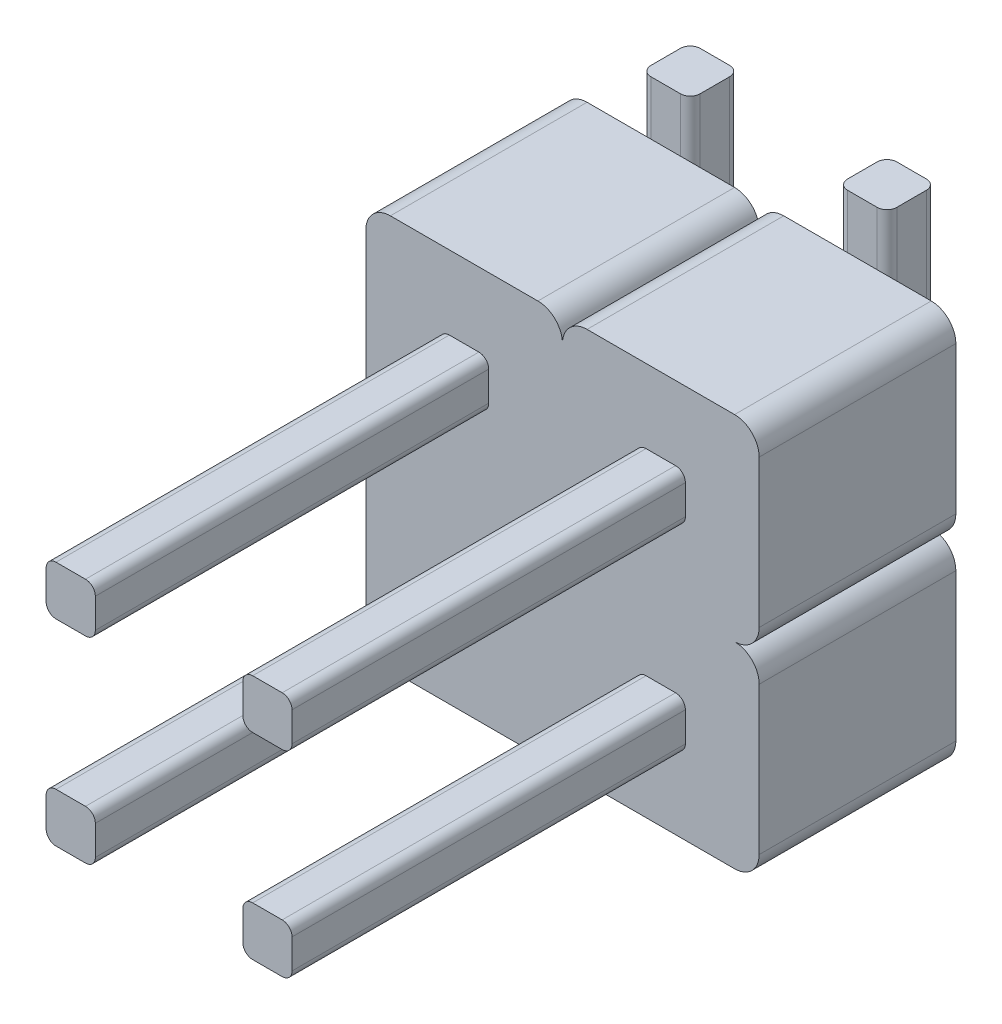
SolidWorks part; units mm, degrees
ref_plane "前视基准面" through (0, 0, 0) normal (0, 0, 1) x (1, 0, 0)
ref_plane "上视基准面" through (0, 0, 0) normal (0, 1, 0) x (1, 0, 0)
ref_plane "右视基准面" through (0, 0, 0) normal (1, 0, 0) x (0, 0, -1)
sketch "草图1" plane through (0, 0, 0) normal (0, 0, 1) x (1, 0, 0)
  line L0 (1, 0) -> (1, -2) construction
  line L1 (0.25, 0) -> (1.75, 0)
  line L2 (0, -0.25) -> (0, -1.75)
  line L3 (0.25, -2) -> (1.75, -2)
  line L4 (2, -0.25) -> (2, -1.75)
  line L5 (0, -1) -> (2, -1) construction
  line L7 (0.85, -0.75) -> (1.15, -0.75)
  line L8 (0.75, -0.85) -> (0.75, -1.15)
  line L9 (0.85, -1.25) -> (1.15, -1.25)
  line L10 (1.25, -0.85) -> (1.25, -1.15)
  arc A0 (2, -1.75) -> (1.75, -2) centre (1.75, -1.75) cw
  arc A1 (0.25, -2) -> (0, -1.75) centre (0.25, -1.75) cw
  arc A2 (0.25, 0) -> (0, -0.25) centre (0.25, -0.25) ccw
  arc A3 (2, -0.25) -> (1.75, 0) centre (1.75, -0.25) ccw
  circle A4 centre (1, -1) radius 0.25 construction
  arc A5 (0.75, -1.15) -> (0.85, -1.25) centre (0.85, -1.15) ccw
  arc A6 (1.15, -1.25) -> (1.25, -1.15) centre (1.15, -1.15) ccw
  arc A7 (1.25, -0.85) -> (1.15, -0.75) centre (1.15, -0.85) ccw
  arc A8 (0.85, -0.75) -> (0.75, -0.85) centre (0.85, -0.85) ccw
  point P11 (0, 0)
  dimension "D3" = 0.25
  dimension "D4" = 0.5
  dimension "D5" = 0.1
  dimension "D1" = 2
  dimension "D2" = 2
extrude "凸台-拉伸1" add sketch "草图1" along normal blind 2
sketch "草图2" plane through (0, 0, 2) normal (0, 0, 1) x (1, 0, 0)
  line L0 (0.75, -0.85) -> (0.75, -1.15)
  line L1 (0.85, -1.25) -> (1.15, -1.25)
  line L2 (1.25, -1.15) -> (1.25, -0.85)
  line L3 (1.15, -0.75) -> (0.85, -0.75)
  arc A0 (1.25, -1.15) -> (1.15, -1.25) centre (1.15, -1.15) cw
  arc A1 (0.85, -1.25) -> (0.75, -1.15) centre (0.85, -1.15) cw
  arc A2 (1.25, -0.85) -> (1.15, -0.75) centre (1.15, -0.85) ccw
  arc A3 (0.85, -0.75) -> (0.75, -0.85) centre (0.85, -0.85) ccw
  dimension "D1" = 0.1
extrude "凸台-拉伸2" add sketch "草图2" along normal blind 4 and the other way blind 2
pattern_linear "阵列(线性)2" count 2 spacing 2 along (1, 0, 0) count 2 spacing 2 along (0, -1, 0) of "凸台-拉伸1", "凸台-拉伸2"
sketch "草图3" plane through (0, 0, 0) normal (0, 0, -1) x (-1, 0, 0)
  line L0 (-1, 0) -> (-1, -4) construction
  line L1 (-1.75, 0) -> (-0.25, 0) construction
  line L2 (-0.25, -4) -> (-1.75, -4) construction
  line L3 (0, -1) -> (-2.4529, -1) construction
  line L4 (0, -0.25) -> (0, -1.75) construction
  line L5 (-0.25, -2) -> (-1.75, -2) construction
  line L9 (-0.75, -0.85) -> (-0.75, -1.15)
  line L10 (-0.85, -1.25) -> (-1.15, -1.25)
  line L11 (-1.25, -0.85) -> (-1.25, -1.15)
  line L12 (-0.85, -0.75) -> (-1.15, -0.75)
  arc A4 (-1.25, -1.15) -> (-1.15, -1.25) centre (-1.15, -1.15) ccw
  arc A5 (-0.75, -1.15) -> (-0.85, -1.25) centre (-0.85, -1.15) cw
  arc A6 (-0.85, -0.75) -> (-0.75, -0.85) centre (-0.85, -0.85) cw
  arc A7 (-1.15, -0.75) -> (-1.25, -0.85) centre (-1.15, -0.85) ccw
  point P26 (-1, -1.25)
  point P28 (-0.75, -1)
  point P29 (-1.25, -1)
  point P31 (-1.25, -1.25)
  point P34 (-0.75, -1.25)
  point P37 (-0.75, -0.75)
  point P40 (-1.25, -0.75)
  dimension "D4" = 0.1
  dimension "D2" = 0.5
  dimension "D3" = 0.5
ref_plane "基准面1" through (1, 0, 0) normal (-1, 0, 0) x (0, 0, 1)
sketch "草图4" plane through (1, 0, 0) normal (-1, 0, 0) x (0, 0, 1)
  line L0 (0, -1.2503) -> (-0.45, -1.2503)
  line L1 (-0.55, -1.1503) -> (-0.55, 0.5)
  line L2 (0, 0) -> (0, -4) construction
  line L3 (0, 0) -> (0, -2) construction
  line L5 (-1.9741, 0.5) -> (2.5979, 0.5) construction
  line L6 (2, 0) -> (0, 0) construction
  arc A0 (-0.45, -1.2503) -> (-0.55, -1.1503) centre (-0.45, -1.1503) cw
  dimension "D3" = 0.1
  dimension "D1" = 0.55
  dimension "D2" = 0.5
ref_plane "基准面2" through (0, -2, 0) normal (0, -1, 0) x (1, 0, 0)
sweep "扫描2" add profiles "草图3" path "草图4"
mirror "镜向5" about plane through (0, -2, 0) normal (0, -1, 0) of "扫描2"
pattern_linear "阵列(线性)10" count 2 spacing 2 along (1, 0, 0) of "扫描2", "镜向5"
